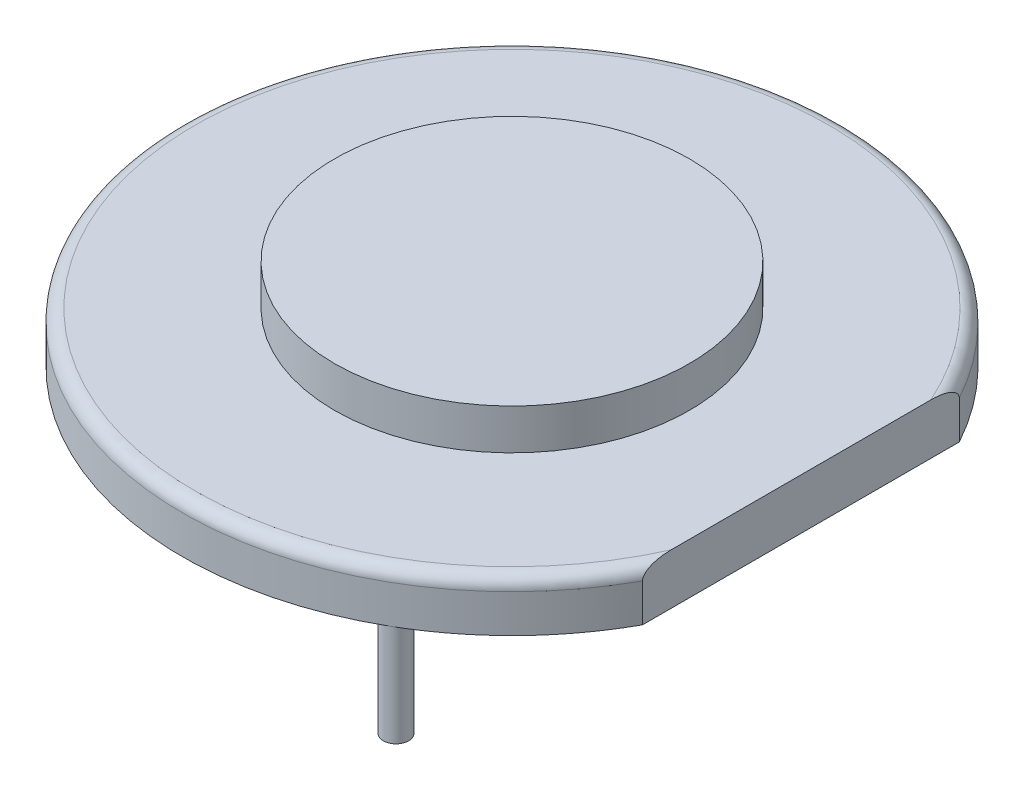
SolidWorks part; units mm, degrees
material "Acrylic (Medium-high impact)"
ref_plane "Front Plane" through (0, 0, 0) normal (0, 0, 1) x (1, 0, 0)
ref_plane "Top Plane" through (0, 0, 0) normal (0, 1, 0) x (1, 0, 0)
ref_plane "Right Plane" through (0, 0, 0) normal (1, 0, 0) x (0, 0, -1)
sketch "Sketch1" plane through (0, 0, 0) normal (0, 1, 0) x (1, 0, 0)
  circle A0 centre (0, 0) radius 3.5
  dimension "D1" = 7
extrude "Boss-Extrude1" add sketch "Sketch1" along normal blind 0.8
sketch "Sketch2" plane through (0, 0, 0) normal (0, -1, 0) x (1, 0, 0)
  circle A0 centre (0, 0) radius 6.5
  dimension "D1" = 13
extrude "Boss-Extrude2" add sketch "Sketch2" along normal blind 1
sketch "Sketch3" plane through (0, -1, 0) normal (0, -1, 0) x (1, 0, 0)
  line L0 (0, 0) -> (5.7, 0)
  line L1 (5.7, 0) -> (5.7, 3.1241)
  line L2 (5.7, 3.1241) -> (5.7, -3.1241)
  circle A0 centre (0, 0) radius 6.5 construction
  arc A1 (5.7, 3.1241) -> (5.7, -3.1241) centre (0, 0) cw
  circle M2 centre (0, 0) radius 6.5
  dimension "D1" = 5.7
extrude "Cut-Extrude1" cut sketch "Sketch3" against normal blind 1 contours L1 L2 M2
sketch "Sketch7" plane through (0, -1, 0) normal (0, -1, 0) x (1, 0, 0)
  line L0 (0, 0) -> (-6.25, 0)
  line L1 (0, 0) -> (3.125, 5.4127)
  line L2 (0, 0) -> (3.125, -5.4127)
  circle A0 centre (-6.25, 0) radius 0.25
  circle A1 centre (3.125, 5.4127) radius 0.25
  circle A2 centre (3.125, -5.4127) radius 0.25
  dimension "D6" = 0.5
  dimension "D7" = 0.5
  dimension "D8" = 0.5
  dimension "D1" = 6.25
  dimension "D2" = 6.25
  dimension "D3" = 6.25
  dimension "D4" = 120
  dimension "D5" = 120
extrude "Boss-Extrude6" add sketch "Sketch7" along normal blind 2
fillet "Fillet2" radius 0.25 1 edges at (-6.5, 0, 0)
